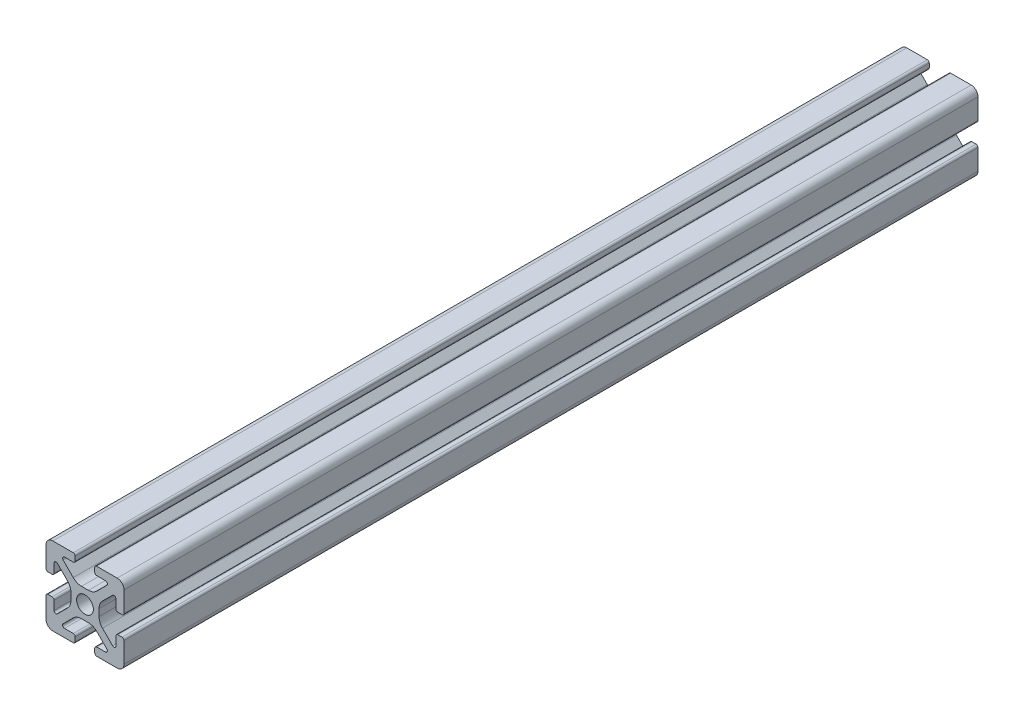
SolidWorks part; units mm, degrees
material "1060 Alloy"
ref_plane "Front Plane" through (0, 0, 0) normal (0, 0, 1) x (1, 0, 0)
ref_plane "Top Plane" through (0, 0, 0) normal (0, 1, 0) x (1, 0, 0)
ref_plane "Right Plane" through (0, 0, 0) normal (1, 0, 0) x (0, 0, -1)
sketch "Sketch2" plane through (0, 0, 0) normal (0, 0, 1) x (1, 0, 0)
  line L0 (0, 10) -> (0, -10) construction
  line L1 (-10, 0) -> (10, 0) construction
  line L2 (2.5, -10) -> (10, -10)
  line L3 (10, -10) -> (10, -2.5)
  line L4 (2.5, -10) -> (2.5, -7.9246)
  line L5 (2.5, -7.9246) -> (6.4571, -7.9246)
  line L6 (6.4571, -7.9246) -> (2.1325, -3.6)
  line L7 (0, 0) -> (10, -10) construction
  line L8 (10, -2.5) -> (7.9246, -2.5)
  line L9 (7.9246, -2.5) -> (7.9246, -6.4571)
  line L10 (7.9246, -6.4571) -> (3.6, -2.1325)
  line L11 (5.7623, -4.2948) -> (4.2948, -5.7623) construction
  circle A0 centre (0, 0) radius 2.15
  arc A1 (5.25, -7.9246) -> (5.6036, -7.0711) centre (5.25, -7.4246) ccw construction
  point P8 (0, -3.6)
  point P16 (5.0286, -5.0286)
  dimension "Center Hole Diameter" = 4.3
  dimension "D3" = 0.5
  dimension "Rail Height" = 20
  dimension "Rail Width" = 20
  dimension "T-Slot Width" = 5
  dimension "Slot Depth" = 6.4
  dimension "Slot Inner Width" = 11.5
sketch "Sketch3" plane through (0, 0, 0) normal (1, 0, 0) x (0, 0, -1)
  line L0 (-609.6, -10) -> (609.6, -10) construction
  line L1 (-584.2, 0) -> (584.2, 0) construction
  line L2 (0, 10) -> (0, -10) construction
  line L3 (0, 10) -> (0, -10) construction
  point P6 (-584.2, 0)
  point P8 (584.2, 0)
  dimension "D1" = 25.4
  dimension "Length" = 1219.2
sketch "Sketch4" plane through (0, 0, 0) normal (0, 0, 1) x (1, 0, 0)
  line L0 (3, -10) -> (8.25, -10)
  line L1 (2.5, -10) -> (10, -10) construction
  line L2 (2.5, -10) -> (2.5, -7.9246) construction
  line L3 (2.5, -7.9246) -> (6.4571, -7.9246) construction
  line L4 (2.5, -8.4246) -> (2.5, -9.5)
  line L5 (3, -7.9246) -> (5.25, -7.9246)
  line L6 (0, -3.6) -> (0.8898, -3.6)
  line L7 (6.4571, -7.9246) -> (2.1325, -3.6) construction
  line L8 (3.0112, -4.4787) -> (5.6036, -7.0711)
  line L9 (10, -10) -> (10, -2.5) construction
  line L10 (7.9246, -6.4571) -> (3.6, -2.1325) construction
  line L11 (7.9246, -2.5) -> (7.9246, -6.4571) construction
  line L12 (7.9246, -5.25) -> (7.9246, -3)
  line L13 (10, -2.5) -> (7.9246, -2.5) construction
  line L14 (8.4246, -2.5) -> (9.5, -2.5)
  line L15 (10, -3) -> (10, -8.25)
  line L16 (7.0711, -5.6036) -> (4.4787, -3.0112)
  line L17 (3.6, 0) -> (3.6, -0.8898)
  line L18 (-10, 0) -> (10, 0) construction
  line L19 (0, -3.6) -> (0, -2.15)
  line L20 (0, 10) -> (0, -10) construction
  line L21 (3.6, 0) -> (2.15, 0)
  arc A0 (2.5, -9.5) -> (3, -10) centre (3, -9.5) ccw
  arc A1 (5.25, -7.9246) -> (5.6036, -7.0711) centre (5.25, -7.4246) ccw construction
  arc A2 (2.5, -8.4246) -> (3, -7.9246) centre (3, -8.4246) cw
  arc A3 (5.25, -7.9246) -> (5.6036, -7.0711) centre (5.25, -7.4246) ccw
  arc A4 (0.8898, -3.6) -> (3.0112, -4.4787) centre (0.8898, -6.6) cw
  arc A5 (8.25, -10) -> (10, -8.25) centre (8.25, -8.25) ccw
  arc A6 (7.0711, -5.6036) -> (7.9246, -5.25) centre (7.4246, -5.25) ccw
  arc A7 (7.9246, -3) -> (8.4246, -2.5) centre (8.4246, -3) cw
  arc A8 (9.5, -2.5) -> (10, -3) centre (9.5, -3) cw
  arc A9 (4.4787, -3.0112) -> (3.6, -0.8898) centre (6.6, -0.8898) cw
  circle A10 centre (0, 0) radius 2.15 construction
  arc A11 (0, -2.15) -> (2.15, 0) centre (0, 0) ccw
  dimension "D1" = 1.75
  dimension "D2" = 3
extrude "Boss-Extrude1" add sketch "Sketch4" along normal mid plane 219
mirror "Mirror1" about plane through (0, 0, 0) normal (1, 0, 0) of bodies 134
mirror "Mirror2" about plane through (0, 0, 0) normal (0, 1, 0) of bodies 135
equation "\"D3@Sketch2\"=\"T-Slot Width@Sketch2\"*0.1"
equation "\"D1@Sketch4\"=\"D3@Sketch2\"*3.5"
equation "\"D2@Sketch4\"=\"D3@Sketch2\"*6"
